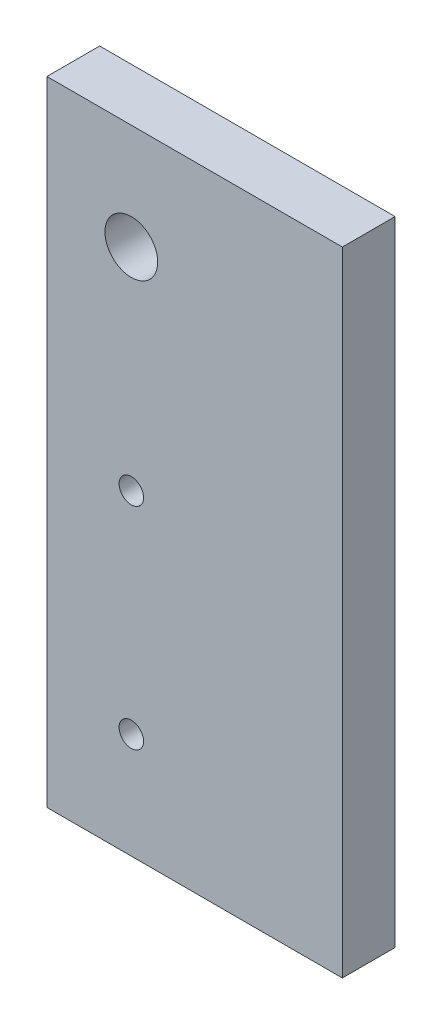
SolidWorks part; units mm, degrees
material "Acrylic (Medium-high impact)"
ref_plane "Front Plane" through (0, 0, 0) normal (0, 0, 1) x (1, 0, 0)
ref_plane "Top Plane" through (0, 0, 0) normal (0, 1, 0) x (1, 0, 0)
ref_plane "Right Plane" through (0, 0, 0) normal (1, 0, 0) x (0, 0, -1)
sketch "Sketch1" plane through (0, 0, 0) normal (0, 0, 1) x (1, 0, 0)
  line L1 (0, 0) -> (35.56, 0)
  line L2 (0, 0) -> (0, 76.2)
  line L3 (0, 76.2) -> (35.56, 76.2)
  line L4 (35.56, 0) -> (35.56, 76.2)
  dimension "D1" = 76.2
  dimension "D2" = 35.56
extrude "Boss-Extrude1" add sketch "Sketch1" along normal blind 6.35
sketch "Sketch3" plane through (0, 0, 6.35) normal (0, 0, 1) x (1, 0, 0)
  line L0 (35.56, 76.2) -> (0, 76.2) construction
  line L1 (35.56, 0) -> (35.56, 76.2) construction
  line L2 (0, 0) -> (35.56, 0) construction
  circle A0 centre (10.16, 63.5) radius 3.175
  circle A1 centre (10.16, 38.1) radius 1.4732
  circle A2 centre (10.16, 12.7) radius 1.4732
  dimension "D1" = 12.7
  dimension "D3" = 6.35
  dimension "D4" = 2.9464
  dimension "D5" = 2.9464
  dimension "D2" = 25.4
  dimension "D6" = 12.7
  dimension "D7" = 25.4
extrude "Cut-Extrude1" cut sketch "Sketch3" against normal through all
